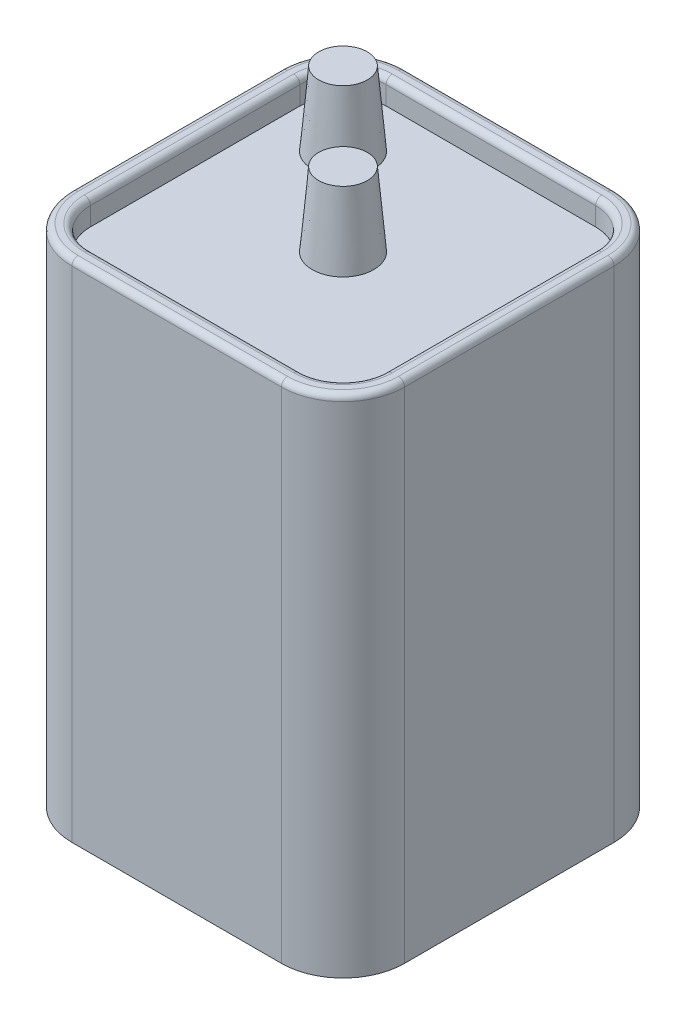
SolidWorks part; units mm, degrees
ref_plane "Front Plane" through (0, 0, 0) normal (0, 0, 1) x (1, 0, 0)
ref_plane "Top Plane" through (0, 0, 0) normal (0, 1, 0) x (1, 0, 0)
ref_plane "Right Plane" through (0, 0, 0) normal (1, 0, 0) x (0, 0, -1)
sketch "Sketch1" plane through (0, 0, 0) normal (0, 1, 0) x (1, 0, 0)
  line L1 (-34.29, 34.29) -> (34.29, 34.29)
  line L2 (-34.29, 34.29) -> (-34.29, -34.29)
  line L3 (-34.29, -34.29) -> (34.29, -34.29)
  line L4 (34.29, 34.29) -> (34.29, -34.29)
  line L5 (-34.29, 34.29) -> (34.29, -34.29) construction
  line L6 (-34.29, -34.29) -> (34.29, 34.29) construction
  point P0 (0, 0)
  dimension "D1" = 68.58
  dimension "D2" = 68.58
extrude "Base Extrude" add sketch "Sketch1" along normal blind 104.14
fillet "Side Fillet" radius 12.7 4 edges at (-34.29, 52.07, 34.29) (34.29, 52.07, 34.29) (34.29, 52.07, -34.29) (-34.29, 52.07, -34.29)
sketch "Sketch2" plane through (0, 104.14, 0) normal (0, 1, 0) x (1, 0, 0)
  line L12 (-30.48, 21.59) -> (-30.48, -21.59)
  line L13 (-21.59, -30.48) -> (21.59, -30.48)
  line L14 (30.48, -21.59) -> (30.48, 21.59)
  line L15 (21.59, 30.48) -> (-21.59, 30.48)
  line L16 (-30.48, 21.59) -> (-30.48, -21.59)
  line L17 (-21.59, -30.48) -> (21.59, -30.48)
  line L18 (30.48, -21.59) -> (30.48, 21.59)
  line L19 (21.59, 30.48) -> (-21.59, 30.48)
  arc A12 (-30.48, -21.59) -> (-21.59, -30.48) centre (-21.59, -21.59) ccw
  arc A13 (21.59, -30.48) -> (30.48, -21.59) centre (21.59, -21.59) ccw
  arc A14 (30.48, 21.59) -> (21.59, 30.48) centre (21.59, 21.59) ccw
  arc A15 (-21.59, 30.48) -> (-30.48, 21.59) centre (-21.59, 21.59) ccw
  arc A16 (-30.48, -21.59) -> (-21.59, -30.48) centre (-21.59, -21.59) ccw
  arc A17 (21.59, -30.48) -> (30.48, -21.59) centre (21.59, -21.59) ccw
  arc A18 (30.48, 21.59) -> (21.59, 30.48) centre (21.59, 21.59) ccw
  arc A19 (-21.59, 30.48) -> (-30.48, 21.59) centre (-21.59, 21.59) ccw
  dimension "D1" = 3.81
extrude "Top Cut" cut sketch "Sketch2" against normal blind 5.08
fillet "Fillet 2" radius 1.27 16 edges at (-30.5703, 104.14, -30.5703) (0, 104.14, -34.29) (30.5703, 104.14, -30.5703) (34.29, 104.14, 0) (30.5703, 104.14, 30.5703) (0, 104.14, 34.29) (-30.5703, 104.14, 30.5703) (-34.29, 104.14, 0) (-30.48, 104.14, 0) (-27.8762, 104.14, 27.8762) (0, 104.14, 30.48) (27.8762, 104.14, 27.8762) (30.48, 104.14, 0) (27.8762, 104.14, -27.8762) (0, 104.14, -30.48) (-27.8762, 104.14, -27.8762)
sketch "Sketch-TERMINALS" plane through (0, 99.06, 0) normal (0, 1, 0) x (1, 0, 0)
  line L0 (-17.9605, 17.9605) -> (0, 0) construction
  circle A0 centre (0, 0) radius 6.35
  circle A1 centre (-17.9605, 17.9605) radius 6.35
  dimension "D1" = 12.7
  dimension "D2" = 25.4
extrude "Termials" add sketch "Sketch-TERMINALS" along normal blind 15.24 draft 5
